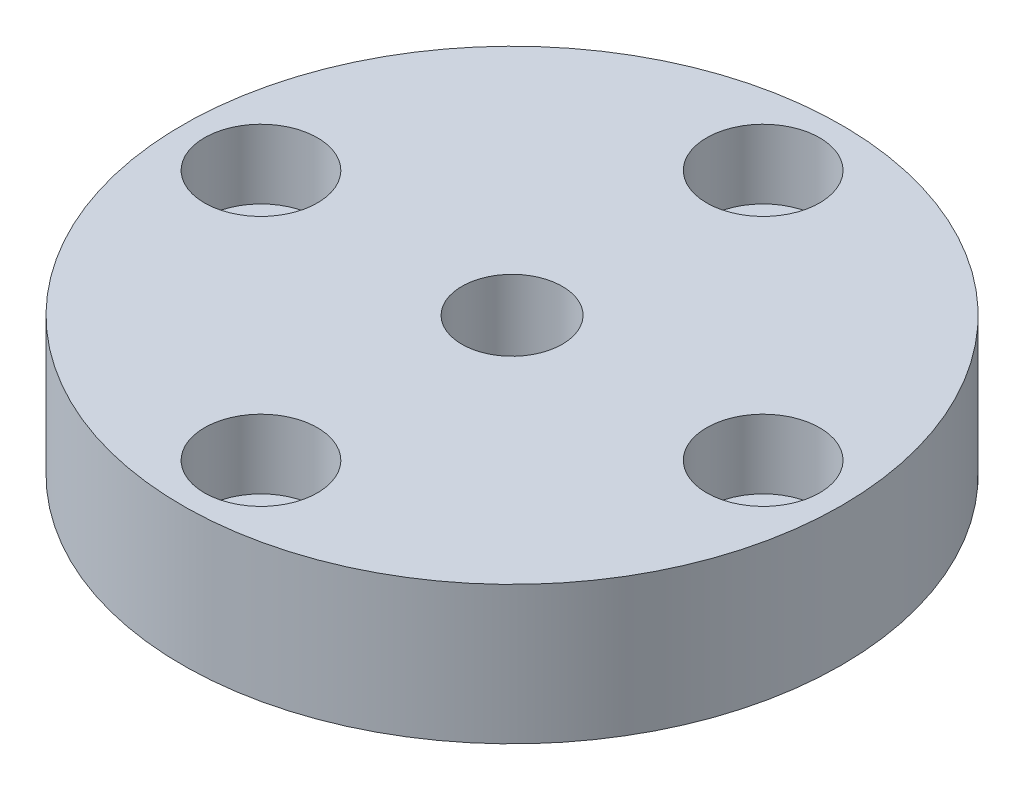
SolidWorks part; units mm, degrees
material "AISI 1020"
ref_plane "Plan de face" through (0, 0, 0) normal (0, 0, 1) x (1, 0, 0)
ref_plane "Plan de dessus" through (0, 0, 0) normal (0, 1, 0) x (1, 0, 0)
ref_plane "Plan de droite" through (0, 0, 0) normal (1, 0, 0) x (0, 0, -1)
sketch "Esquisse1" plane through (0, 0, 0) normal (0, 0, 1) x (1, 0, 0)
  line L0 (0, -750.9271) -> (0, 36795.4265) construction
  line L1 (8, 0) -> (8, 27)
  line L2 (8, 27) -> (52.5, 27)
  line L3 (52.5, 27) -> (52.5, 5)
  line L4 (52.5, 5) -> (25, 5)
  line L5 (25, 5) -> (25, 0)
  line L6 (25, 0) -> (8, 0)
  dimension "D1" = 27
  dimension "D2" = 5
  dimension "D3" = 105
  dimension "D4" = 16
  dimension "D5" = 50
revolve "Révolution1" add sketch "Esquisse1" angle 360 about L0
sketch "Esquisse2" plane through (0, 27, 0) normal (0, 1, 0) x (1, 0, 0)
  line L0 (-1000, 0) -> (49000, 0) construction
  circle A0 centre (0, 0) radius 40 construction
  dimension "D1" = 80
hole_wizard "Chambrage pour vis à tête cylindrique à 6 pans creux (ou vis CHC) M101" positions "Esquisse6" profile "Esquisse5" counterbore size "M10" standard "Ansi Metric" end condition through all
sketch "Esquisse6" plane through (0, 27, 0) normal (0, 1, 0) x (1, 0, 0)
  circle A0 centre (0, 0) radius 40 construction
  point P0 (-40, 0)
sketch "Esquisse5" plane through (-40, 27, 0) normal (1, 0, 0) x (0, 0, 1)
  line L0 (0, 0) -> (0, 27)
  line L1 (0, 27) -> (5.5, 27)
  line L3 (5.5, 27) -> (5.5, 11)
  line L4 (5.5, 11) -> (9, 11)
  line L5 (9, 11) -> (9, 0)
  line L7 (9, 0) -> (0, 0)
  line L11 (0, -6.35) -> (0, 107.95) construction
  dimension "Diamètre du perçage jusqu'au prochain" = 11
  dimension "Profondeur du perçage jusqu'au prochain" = 27
  dimension "Diamètre du chambrage" = 18
  dimension "Profondeur du chambrage" = 11
pattern_circular "Répétition circulaire1" count 4 every 90 about axis through (0, 0, 0) along (0, 1, 0) of "Chambrage pour vis à tête cylindrique à 6 pans creux (ou vis CHC) M101"
